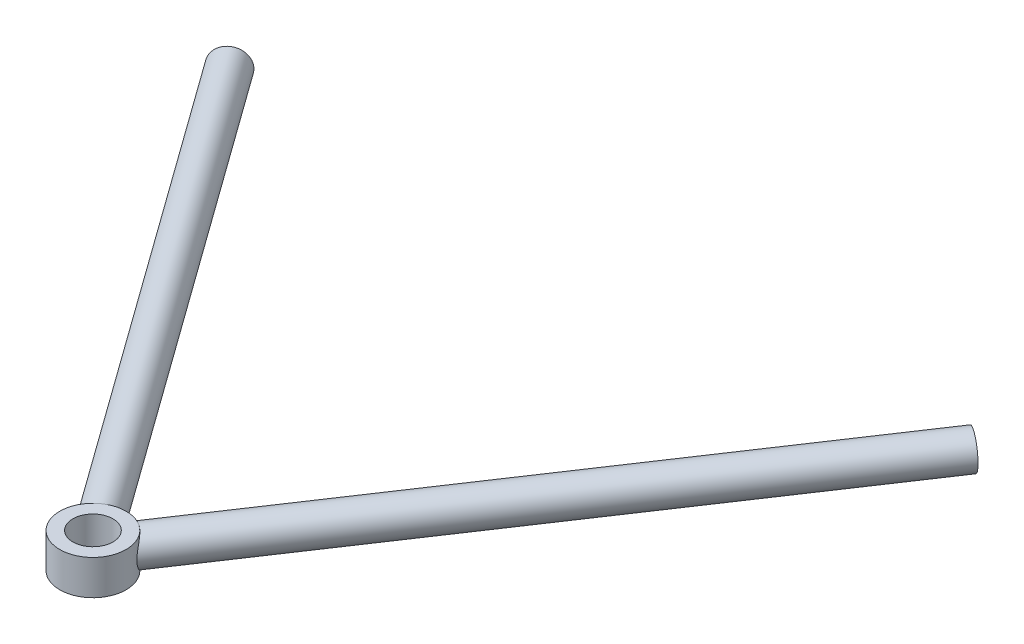
SolidWorks part; units mm, degrees
material "AISI 4130 Steel, annealed at 865C"
ref_plane "Front Plane" through (0, 0, 0) normal (0, 0, 1) x (1, 0, 0)
ref_plane "Top Plane" through (0, 0, 0) normal (0, 1, 0) x (1, 0, 0)
ref_plane "Right Plane" through (0, 0, 0) normal (1, 0, 0) x (0, 0, -1)
sketch "Sketch1" plane through (0, 0, 0) normal (0, 1, 0) x (1, 0, 0)
  circle A0 centre (0, 0) radius 11.5062
  circle A1 centre (0, 0) radius 19.0062
  dimension "D3" = 23.0124
  dimension "D1" = 38.0124
extrude "Boss-Extrude1" add sketch "Sketch1" along normal mid plane 20
sketch "Sketch3" plane through (0, 0, 0) normal (0, 1, 0) x (1, 0, 0)
  line L0 (-19.0062, 0) -> (19.0062, 0) construction
  line L1 (0, 0) -> (-219.5, 305.0017) construction
  line L2 (0, 0) -> (201.8849, 302.3522) construction
  line L3 (-11.102, 15.4266) -> (-219.5, 305.0017) construction
  line L4 (10.5542, 15.8065) -> (201.8849, 302.3522) construction
  line L6 (201.8849, 302.3522) -> (223.5693, 287.8732) construction
  line L7 (-200.9705, 279.2544) -> (-227.4729, 260.1815) construction
  line L8 (0, 0) -> (219.5, 328.7334) construction
  line L9 (-219.5, 305.0017) -> (219.5, 328.7334) construction
  circle A0 centre (0, 0) radius 19.0062 construction
  circle A1 centre (0, 0) radius 19.0062 construction
  dimension "D1" = 54.259
  dimension "D2" = 56.268
  dimension "D3" = 375.7743
  dimension "D5" = 31.7217
  dimension "D4" = 395.2795
  dimension "D6" = 31.7217
ref_plane "tube1plane" through (201.8849, 0, -302.3522) normal (0.5553, 0, -0.8316) x (0.8316, 0, 0.5553)
ref_plane "tube2plane" through (-200.9705, 0, -279.2544) normal (-0.5841, 0, -0.8117) x (-0.8117, 0, 0.5841)
sketch "Sketch5" plane through (201.8849, 0, -302.3522) normal (0.5553, 0, -0.8316) x (0.8316, 0, 0.5553)
  circle A0 centre (0, 0) radius 10
  circle A1 centre (0, 0) radius 7
  dimension "D1" = 20
  dimension "D2" = 14
extrude "Boss-Extrude2" add sketch "Sketch5" against normal up to next
sketch "Sketch6" plane through (-200.9705, 0, -279.2544) normal (-0.5841, 0, -0.8117) x (-0.8117, 0, 0.5841)
  circle A0 centre (0, 0) radius 10
  circle A1 centre (0, 0) radius 7
  dimension "D1" = 20
  dimension "D2" = 14
extrude "Boss-Extrude3" add sketch "Sketch6" against normal up to surface (327.8898 mm away)
equation "\"CA_ID\"= 14"
equation "\"D2@Sketch5\"=\"CA_ID\""
equation "\"D2@Sketch6\"=\"CA_ID\""
equation "\"tube_end_to_ball_center\" = 31.721675mm"
equation "\"D6@Sketch3\"=\"tube_end_to_ball_center\""
equation "\"D5@Sketch3\"=\"tube_end_to_ball_center\""
